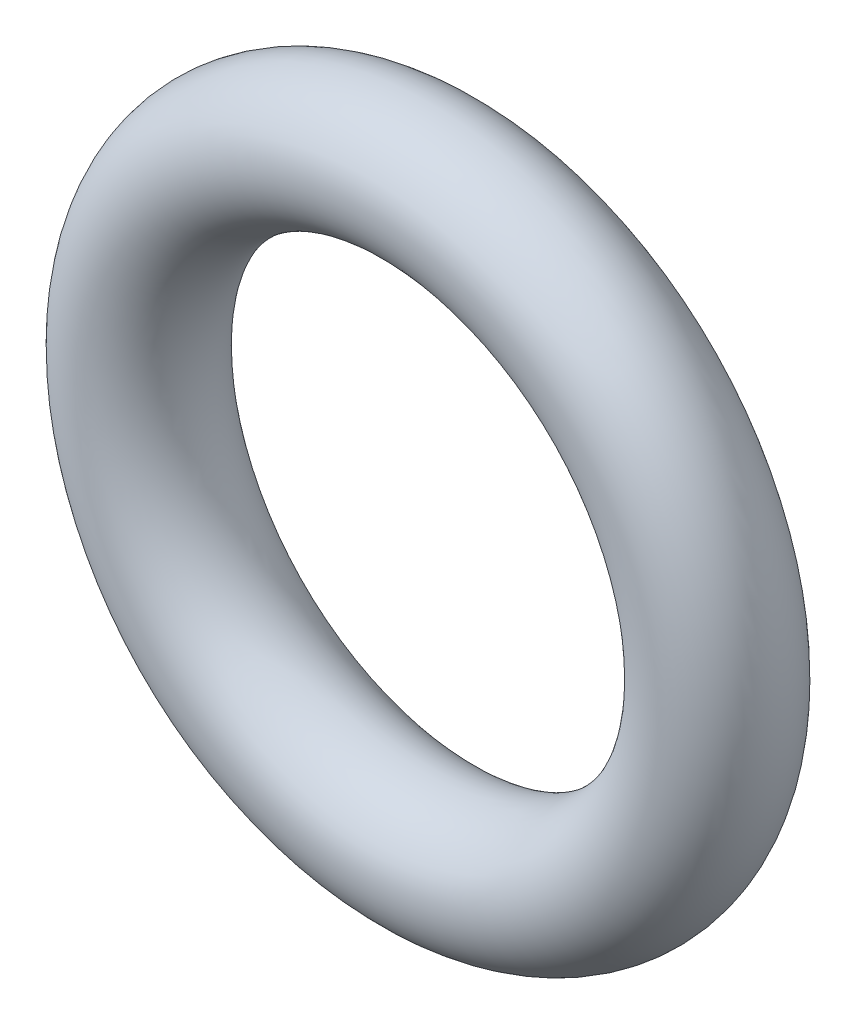
SolidWorks part; units mm, degrees
ref_plane "Front" through (0, 0, 0) normal (0, 0, 1) x (1, 0, 0)
ref_plane "Top" through (0, 0, 0) normal (0, 1, 0) x (1, 0, 0)
ref_plane "Right" through (0, 0, 0) normal (1, 0, 0) x (0, 0, -1)
sketch "Sketch1" plane through (0, 0, 0) normal (1, 0, 0) x (0, -1, 0)
  line L0 (0, -0.889) -> (0, 0.889) construction
  line L2 (-5.2946, 0) -> (5.2946, 0) construction
  line L3 (-3.0353, 0) -> (3.0353, 0) construction
  circle A0 centre (3.9243, 0) radius 0.889
  point P9 (3.0353, 0)
  point P10 (4.8133, 0)
  point P13 (3.9243, 0.889)
  point P14 (3.9243, -0.889)
  dimension "Width" = 1.778
  dimension "ID" = 6.0706
revolve "Revolve1" add sketch "Sketch1" angle 360 about L0
